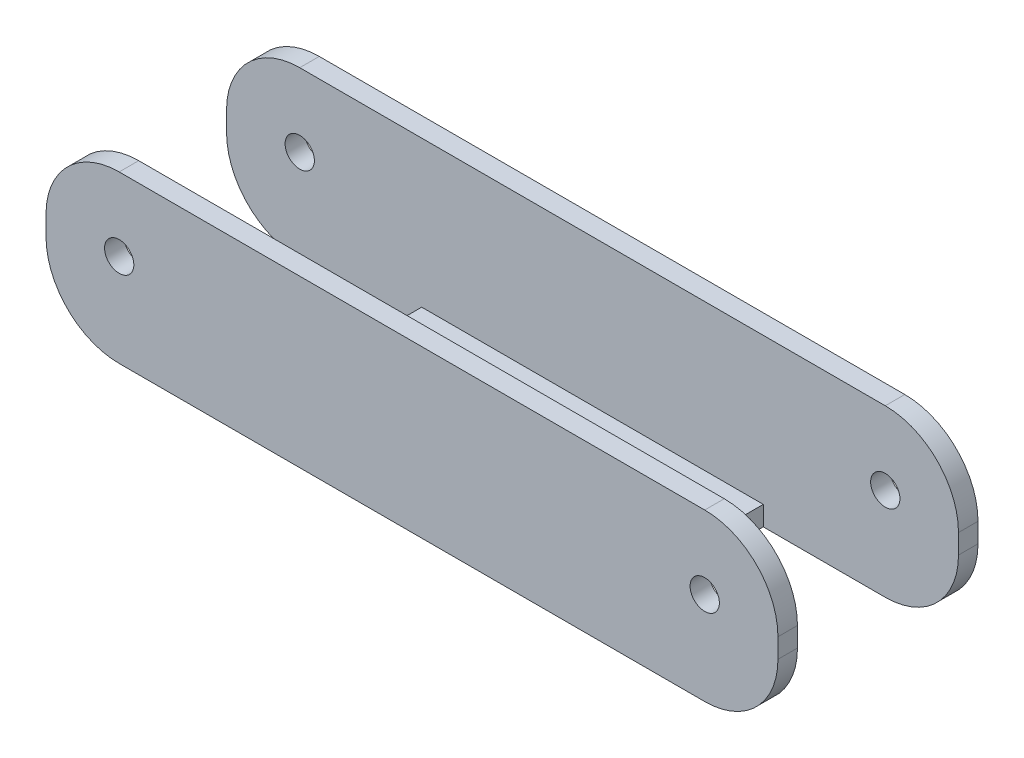
SolidWorks part; units mm, degrees
ref_plane "前视基准面" through (0, 0, 0) normal (0, 0, 1) x (1, 0, 0)
ref_plane "上视基准面" through (0, 0, 0) normal (0, 1, 0) x (1, 0, 0)
ref_plane "右视基准面" through (0, 0, 0) normal (1, 0, 0) x (0, 0, -1)
sketch "草图1" plane through (0, 0, 0) normal (1, 0, 0) x (0, 0, -1)
  line L0 (0, 43.3361) -> (0, -38.7973) construction
  line L1 (-16.5, 34) -> (-20.5, 34)
  line L2 (-20.5, 34) -> (-20.5, 0)
  line L3 (-20.5, 0) -> (20.5, 0)
  line L4 (0, 0) -> (0, 4)
  line L5 (16.5, 4) -> (-16.5, 4)
  line L6 (-16.5, 4) -> (-16.5, 34)
  line L7 (16.5, 4) -> (16.5, 34)
  line L8 (20.5, 34) -> (20.5, 0)
  line L9 (16.5, 34) -> (20.5, 34)
  dimension "D1" = 4
  dimension "D2" = 4
  dimension "D3" = 16.5
  dimension "D4" = 30
extrude "凸台-拉伸1" add sketch "草图1" along normal blind 150 contours L5 L6 L1 L2 L3 L4 | L9 L7 L5 L4 L3 L8
sketch "草图2" plane through (0, 0, 20.5) normal (0, 0, 1) x (1, 0, 0)
  line L0 (75, 34) -> (75, -88.1355) construction
  line L1 (150, 34) -> (0, 34) construction
  line L2 (150, 4) -> (0, 4) construction
  circle A0 centre (15, 19) radius 3
  circle A1 centre (135, 19) radius 3
  dimension "D1" = 6
  dimension "D2" = 60
  dimension "D3" = 15
extrude "切除-拉伸1" cut sketch "草图2" against normal blind 300
sketch "草图3" plane through (0, 0, 0) normal (0, -1, 0) x (1, 0, 0)
  line L0 (150, 16.5) -> (150, -16.5)
  line L1 (150, 20.5) -> (150, -20.5) construction
  line L2 (150, -16.5) -> (110, -16.5)
  line L3 (110, -16.5) -> (110, 16.5)
  line L4 (110, 16.5) -> (150, 16.5)
  line L5 (150, 20.5) -> (0, 20.5) construction
  line L6 (150, -20.5) -> (0, -20.5) construction
  line L7 (75, 20.5) -> (75, -125.7176) construction
  line L8 (40, 16.5) -> (0, 16.5)
  line L9 (40, -16.5) -> (40, 16.5)
  line L10 (0, -16.5) -> (40, -16.5)
  line L11 (0, 16.5) -> (0, -16.5)
  dimension "D1" = 4
  dimension "D2" = 4
  dimension "D3" = 40
extrude "切除-拉伸2" cut sketch "草图3" against normal blind 10
fillet "圆角1" radius 15 8 edges at (0, 0, 18.5) (0, 34, 18.5) (150, 34, 18.5) (150, 0, 18.5) (150, 34, -18.5) (150, 0, -18.5) (0, 0, -18.5) (0, 34, -18.5)
